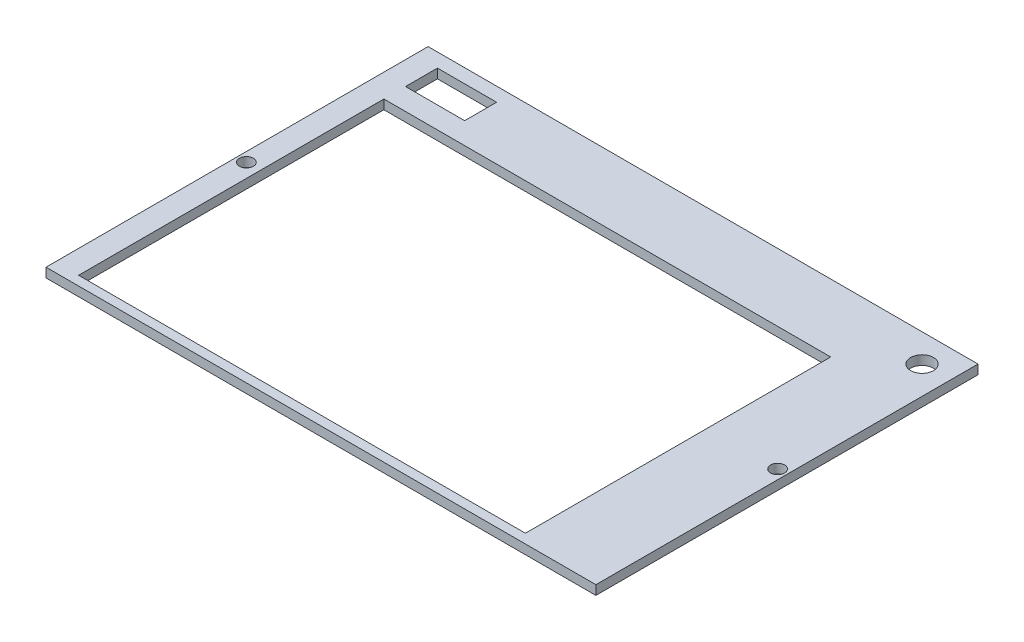
SolidWorks part; units mm, degrees
ref_plane "Front Plane" through (0, 0, 0) normal (0, 0, 1) x (1, 0, 0)
ref_plane "Top Plane" through (0, 0, 0) normal (0, 1, 0) x (1, 0, 0)
ref_plane "Right Plane" through (0, 0, 0) normal (1, 0, 0) x (0, 0, -1)
sketch "Sketch1" plane through (0, 0, 0) normal (0, 1, 0) x (1, 0, 0)
  line L1 (-59, -41) -> (59, -41)
  line L2 (-59, -41) -> (-59, 41)
  line L3 (-59, 41) -> (59, 41)
  line L4 (59, -41) -> (59, 41)
  line L5 (-59, -41) -> (59, 41) construction
  line L6 (-59, 41) -> (59, -41) construction
  point P0 (0, 0)
  dimension "D1" = 118
  dimension "D2" = 82
extrude "Boss-Extrude1" add sketch "Sketch1" along normal blind 2
sketch "Sketch2" plane through (0, 2, 0) normal (0, 1, 0) x (1, 0, 0)
  line L0 (-59, 41) -> (-59, -41) construction
  line L1 (-54, -39) -> (41.88, -39)
  line L2 (-54, -39) -> (-54, 26.51)
  line L3 (-54, 26.51) -> (41.88, 26.51)
  line L4 (41.88, -39) -> (41.88, 26.51)
  line L5 (-59, -41) -> (59, -41) construction
  line L6 (59, 41) -> (-59, 41) construction
  line L7 (-54, 38) -> (-41.31, 38)
  line L8 (-54, 38) -> (-54, 31.15)
  line L9 (-54, 31.15) -> (-41.31, 31.15)
  line L10 (-41.31, 38) -> (-41.31, 31.15)
  line L11 (59, -41) -> (59, 41) construction
  circle A0 centre (53, 35) radius 2.45
  dimension "D9" = 4.9
  dimension "D10" = 6
  dimension "D1" = 95.88
  dimension "D2" = 65.51
  dimension "D3" = 5
  dimension "D4" = 2
  dimension "D5" = 12.69
  dimension "D6" = 6.85
  dimension "D7" = 5
  dimension "D8" = 3
  dimension "D11" = 6
sketch "Sketch3" plane through (0, 2, 0) normal (0, 1, 0) x (1, 0, 0)
  line L0 (59, -41) -> (59, 41) construction
  line L1 (0, 17.2901) -> (0, -11.6174) construction
  line L2 (-59, 41) -> (-59, -41) construction
  circle A0 centre (57, 0) radius 1.5
  circle A2 centre (-57, 0) radius 1.5
  point P11 (0, 0)
  dimension "D1" = 3
  dimension "D2" = 2
  dimension "D4" = 2
  dimension "D3" = 3
extrude "Cut-Extrude4" cut sketch "Sketch2" against normal blind 10
extrude "Cut-Extrude7" cut sketch "Sketch3" against normal blind 10
